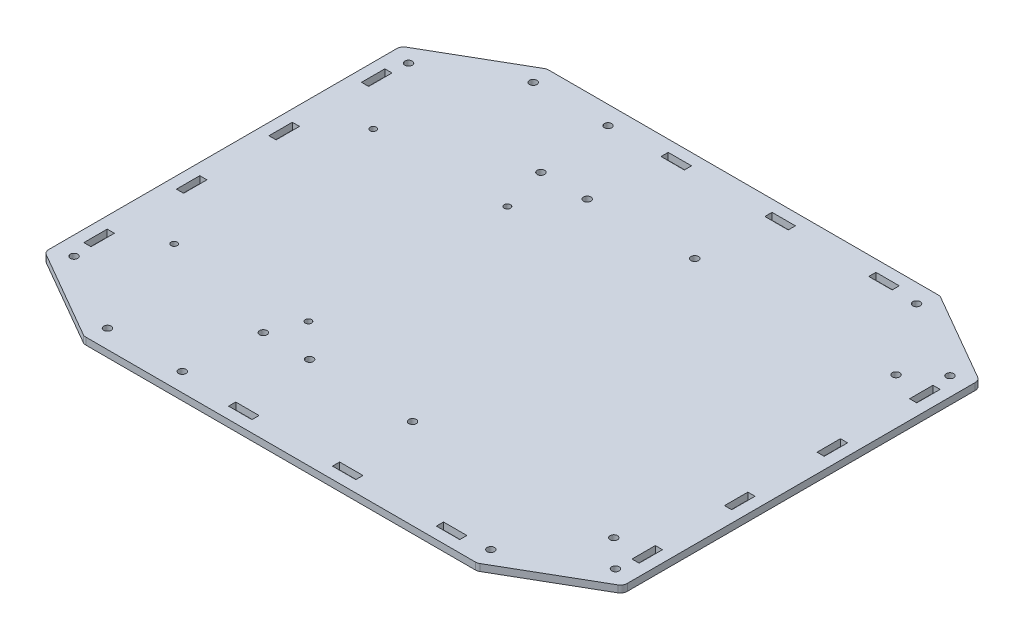
SolidWorks part; units mm, degrees
ref_plane "Front Plane" through (0, 0, 0) normal (0, 0, 1) x (1, 0, 0)
ref_plane "Top Plane" through (0, 0, 0) normal (0, 1, 0) x (1, 0, 0)
ref_plane "Right Plane" through (0, 0, 0) normal (1, 0, 0) x (0, 0, -1)
sketch "Sketch1" plane through (0, 0, 0) normal (0, 1, 0) x (1, 0, 0)
  line L0 (-85, 100) -> (85, 100)
  line L1 (-125, 100) -> (125, 100) construction
  line L2 (-125, 100) -> (-125, -100) construction
  line L3 (-125, -100) -> (125, -100) construction
  line L4 (125, 100) -> (125, -100) construction
  line L5 (85, 100) -> (125, 76.906)
  line L6 (125, 76.906) -> (125, -76.906)
  line L8 (-125, -76.906) -> (-125, 76.906)
  line L9 (-125, 76.906) -> (-85, 100)
  line L10 (-125, 0) -> (125, 0) construction
  line L11 (85, -100) -> (125, -76.906)
  line L12 (-85, -100) -> (85, -100)
  line L13 (-125, -76.906) -> (-85, -100)
  line L14 (0, 100) -> (0, -100) construction
  line L26 (-17.4, -91.9) -> (-27.5, -91.9)
  line L27 (-17.4, -91.9) -> (-17.4, -95)
  line L28 (-17.4, -95) -> (-27.5, -95)
  line L29 (-27.5, -91.9) -> (-27.5, -95)
  line L65 (-118.45, 14.95) -> (-118.45, -14.95) construction
  line L66 (-120, 65.05) -> (-116.9, 65.05)
  line L67 (-120, 65.05) -> (-120, 54.95)
  line L68 (-120, 54.95) -> (-116.9, 54.95)
  line L69 (-116.9, 65.05) -> (-116.9, 54.95)
  line L70 (-120, 25.05) -> (-116.9, 25.05)
  line L71 (-120, 25.05) -> (-120, 14.95)
  line L72 (-120, 14.95) -> (-116.9, 14.95)
  line L73 (-116.9, 25.05) -> (-116.9, 14.95)
  line L74 (-120, -14.95) -> (-116.9, -14.95)
  line L75 (-120, -14.95) -> (-120, -25.05)
  line L76 (-120, -25.05) -> (-116.9, -25.05)
  line L77 (-116.9, -14.95) -> (-116.9, -25.05)
  line L78 (-120, -54.95) -> (-116.9, -54.95)
  line L79 (-120, -54.95) -> (-120, -65.05)
  line L80 (-120, -65.05) -> (-116.9, -65.05)
  line L81 (-116.9, -54.95) -> (-116.9, -65.05)
  line L82 (120, -65.05) -> (116.9, -65.05)
  line L83 (116.9, -54.95) -> (116.9, -65.05)
  line L84 (120, -54.95) -> (116.9, -54.95)
  line L85 (120, -54.95) -> (120, -65.05)
  line L86 (120, -25.05) -> (116.9, -25.05)
  line L87 (116.9, -14.95) -> (116.9, -25.05)
  line L88 (120, -14.95) -> (116.9, -14.95)
  line L89 (120, -14.95) -> (120, -25.05)
  line L90 (120, 14.95) -> (116.9, 14.95)
  line L91 (116.9, 25.05) -> (116.9, 14.95)
  line L92 (120, 25.05) -> (116.9, 25.05)
  line L93 (120, 25.05) -> (120, 14.95)
  line L94 (120, 54.95) -> (116.9, 54.95)
  line L95 (116.9, 65.05) -> (116.9, 54.95)
  line L96 (120, 65.05) -> (116.9, 65.05)
  line L97 (120, 65.05) -> (120, 54.95)
  line L98 (27.5, -91.9) -> (27.5, -95)
  line L99 (27.5, -91.9) -> (17.4, -91.9)
  line L100 (17.4, -91.9) -> (17.4, -95)
  line L101 (27.5, -95) -> (17.4, -95)
  line L102 (72.4, -91.9) -> (72.4, -95)
  line L103 (72.4, -91.9) -> (62.3, -91.9)
  line L104 (62.3, -91.9) -> (62.3, -95)
  line L105 (72.4, -95) -> (62.3, -95)
  line L106 (72.4, 91.9) -> (62.3, 91.9)
  line L107 (62.3, 91.9) -> (62.3, 95)
  line L108 (72.4, 95) -> (62.3, 95)
  line L109 (72.4, 91.9) -> (72.4, 95)
  line L110 (27.5, 91.9) -> (17.4, 91.9)
  line L111 (17.4, 91.9) -> (17.4, 95)
  line L112 (27.5, 95) -> (17.4, 95)
  line L113 (27.5, 91.9) -> (27.5, 95)
  line L114 (-17.4, 95) -> (-27.5, 95)
  line L115 (-27.5, 91.9) -> (-27.5, 95)
  line L116 (-17.4, 91.9) -> (-27.5, 91.9)
  line L117 (-17.4, 91.9) -> (-17.4, 95)
  circle A0 centre (-47.5, -60) radius 1.6 construction
  circle A1 centre (82.8564, 92) radius 1.6 construction
  circle A2 centre (117, 72.2872) radius 1.6 construction
  circle A3 centre (117, -72.2872) radius 1.6 construction
  circle A4 centre (82.8564, -92) radius 1.6 construction
  circle A5 centre (-27.5, -60) radius 1.6 construction
  circle A6 centre (-27.5, 60) radius 1.6 construction
  circle A7 centre (-117, -72.2872) radius 1.6 construction
  circle A8 centre (-50.5, -92) radius 1.6 construction
  circle A9 centre (-47.5, 60) radius 1.6 construction
  circle A10 centre (-117, 72.2872) radius 1.6 construction
  circle A11 centre (-50.5, 92) radius 1.6 construction
  circle A12 centre (-47.5, -60) radius 1.6
  circle A13 centre (82.8564, 92) radius 1.6
  circle A14 centre (117, 72.2872) radius 1.6
  circle A15 centre (117, -72.2872) radius 1.6
  circle A16 centre (82.8564, -92) radius 1.6
  circle A17 centre (-27.5, -60) radius 1.6
  circle A18 centre (-27.5, 60) radius 1.6
  circle A19 centre (-117, -72.2872) radius 1.6
  circle A20 centre (-50.5, -92) radius 1.6
  circle A21 centre (-47.5, 60) radius 1.6
  circle A22 centre (-117, 72.2872) radius 1.6
  circle A23 centre (-50.5, 92) radius 1.6
  circle A24 centre (-82.8564, -92) radius 1.6 construction
  circle A25 centre (-82.8564, 92) radius 1.6 construction
  circle A26 centre (-82.8564, -92) radius 1.6
  circle A27 centre (-82.8564, 92) radius 1.6
  point P4 (0, 100)
  point P6 (-125, 0)
  point P9 (0, 0)
  point P20 (-22.45, -95)
  point P61 (-116.9, 60)
  point P62 (-116.9, 20)
  point P63 (-116.9, -20)
  point P64 (-116.9, -60)
  point P67 (-118.45, 0)
  dimension "D1" = 250
  dimension "D2" = 200
  dimension "D3" = 60
  dimension "D4" = 60
  dimension "D5" = 40
  dimension "D6" = 10.1
  dimension "D7" = 3.1
  dimension "D8" = 22.45
  dimension "D9" = 3
  dimension "D10" = 5
  dimension "D11" = 3.1
  dimension "D12" = 10.1
  dimension "D13" = 5
  dimension "D14" = 40
  dimension "D15" = 40
  dimension "D16" = 40
extrude "Boss-Extrude1" add sketch "Sketch1" along normal blind 3
sketch "Sketch3" plane through (0, 3, 0) normal (0, 1, 0) x (1, 0, 0)
  line B0 (-25, -50) -> (-104, -50) construction
  line B1 (-25, -50) -> (-25, 50) construction
  line B2 (-25, 50) -> (-104, 50) construction
  line B3 (-104, -50) -> (-104, 50) construction
  circle B4 centre (-100, -46) radius 1.35
  circle B5 centre (-42, -46) radius 1.35
  circle B6 centre (-42, 40) radius 1.35
  circle B7 centre (-100, 40) radius 1.35
  line B8 (14, 65) -> (14, -65) construction
  circle B9 centre (18, 61) radius 1.6
  circle B10 centre (105, 61) radius 1.6
  circle B11 centre (105, -61) radius 1.6
  circle B12 centre (18, -61) radius 1.6
  dimension "D1" = 25
  dimension "D2" = 14
sketch_block_instance "Block-Jetson-Nano-1"
sketch_block "Block-Jetson-Nano"
sketch_block_instance "Block-MCU-Board-1"
sketch_block "Block2" parameters "D3"=3.2, "D1"=87, "D2"=122
extrude "Cut-Extrude1" cut sketch "Sketch3" against normal up to next
fillet "Fillet1" radius 3 8 edges at (85, 1.5, -100) (125, 1.5, -76.906) (-85, 1.5, -100) (-125, 1.5, -76.906) (-85, 1.5, 100) (-125, 1.5, 76.906) (85, 1.5, 100) (125, 1.5, 76.906)
